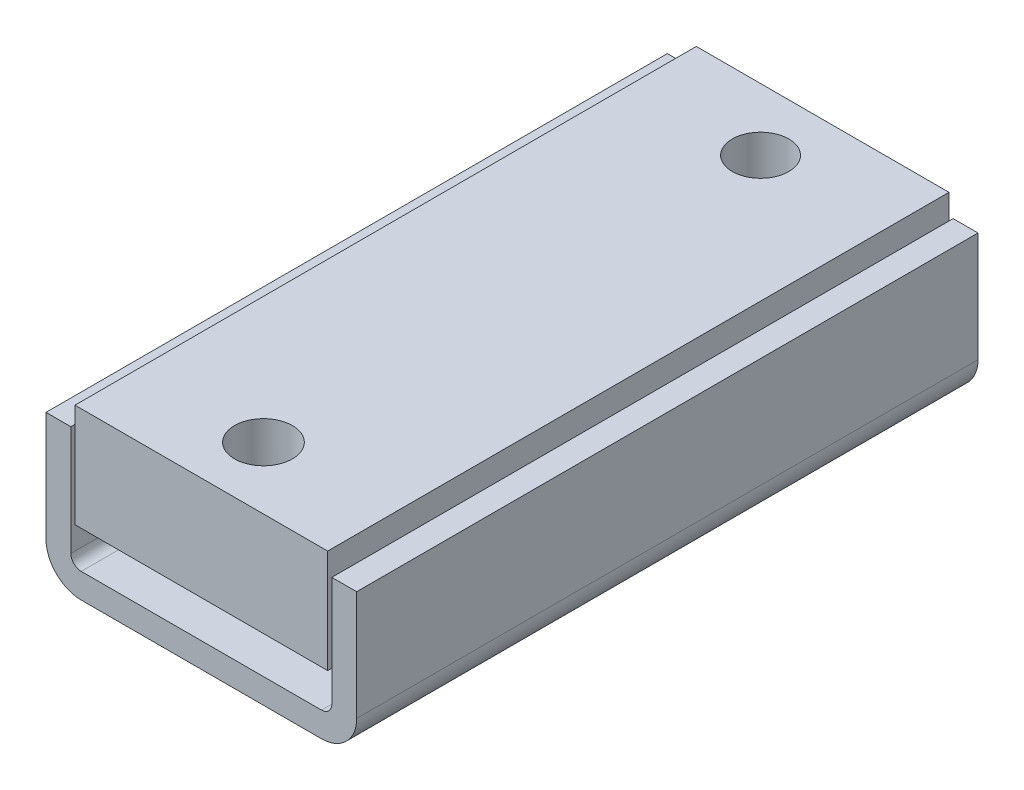
SolidWorks part; units mm, degrees
ref_plane "Plan de face" through (0, 0, 0) normal (0, 0, 1) x (1, 0, 0)
ref_plane "Plan de dessus" through (0, 0, 0) normal (0, 1, 0) x (1, 0, 0)
ref_plane "Plan de droite" through (0, 0, 0) normal (1, 0, 0) x (0, 0, -1)
sketch "Esquisse1" plane through (0, 0, 0) normal (0, 0, 1) x (1, 0, 0)
  line L0 (0, 7) -> (0, 0)
  line L1 (0, 0) -> (15, 0)
  line L2 (15, 0) -> (15, 7)
  line L3 (15, 7) -> (13.8, 7)
  line L4 (13.8, 7) -> (13.8, 1.2)
  line L5 (13.8, 1.2) -> (1.2, 1.2)
  line L6 (1.2, 1.2) -> (1.2, 7)
  line L7 (1.2, 7) -> (0, 7)
  dimension "D1" = 7
  dimension "D2" = 1.2
  dimension "D3" = 1.2
  dimension "D4" = 1.2
  dimension "D5" = 15
extrude "Boss.-Extru.1" add sketch "Esquisse1" along normal blind 30
sketch "Esquisse2" plane through (0, 0, 0) normal (0, -1, 0) x (1, 0, 0)
  line L0 (7.5, 30) -> (7.5, 0) construction
  line L1 (0, 30) -> (15, 30) construction
  line L2 (0, 0) -> (15, 0) construction
  line L3 (5.3311, 22) -> (9.6874, 22) construction
  line L4 (15, 15) -> (0, 15) construction
  line L5 (15, 30) -> (15, 0) construction
  line L6 (0, 30) -> (0, 0) construction
  line L7 (5.3311, 8) -> (9.6874, 8) construction
  circle A0 centre (7.5, 22) radius 1.5
  circle A1 centre (7.5, 8) radius 1.5
  dimension "D2" = 3
  dimension "D1" = 14
extrude "Enlèv. mat.-Extru.1" cut sketch "Esquisse2" against normal through all
fillet "Congé1" radius 0.5 2 edges at (13.8, 1.2, 15) (1.2, 1.2, 15)
fillet "Congé2" radius 1.7 2 edges at (15, 0, 15) (0, 0, 15)
sketch "Esquisse3" plane through (0, 0, 30) normal (0, 0, 1) x (1, 0, 0)
  line L0 (0, 7) -> (15, 7) construction
  line L1 (1.4, 8) -> (13.6, 8)
  line L2 (1.4, 8) -> (1.4, 3)
  line L3 (1.4, 3) -> (13.6, 3)
  line L4 (13.6, 8) -> (13.6, 3)
  line L5 (0, 7) -> (0, 1.7) construction
  line L6 (7.5, 8.8763) -> (7.5, 0) construction
  line L7 (1.7, 0) -> (13.3, 0) construction
  dimension "D1" = 12.2
  dimension "D2" = 1
  dimension "D3" = 4
extrude "Boss.-Extru.2" add sketch "Esquisse3" against normal up to vertex (30 mm away) separate body
sketch "Esquisse4" plane through (0, 8, 0) normal (0, 1, 0) x (1, 0, 0)
  line L0 (7.5, -30) -> (7.5, 0) construction
  line L1 (13.6, -30) -> (1.4, -30) construction
  line L2 (13.6, 0) -> (1.4, 0) construction
  line L3 (1.4, -15) -> (13.6, -15) construction
  line L4 (1.4, 0) -> (1.4, -30) construction
  line L5 (13.6, 0) -> (13.6, -30) construction
  circle A0 centre (7.5, -3) radius 1.3645
  circle A1 centre (7.5, -27) radius 1.3966
  dimension "D1" = 24
extrude "Enlèv. mat.-Extru.2" cut sketch "Esquisse4" against normal up to next (5 mm away)
